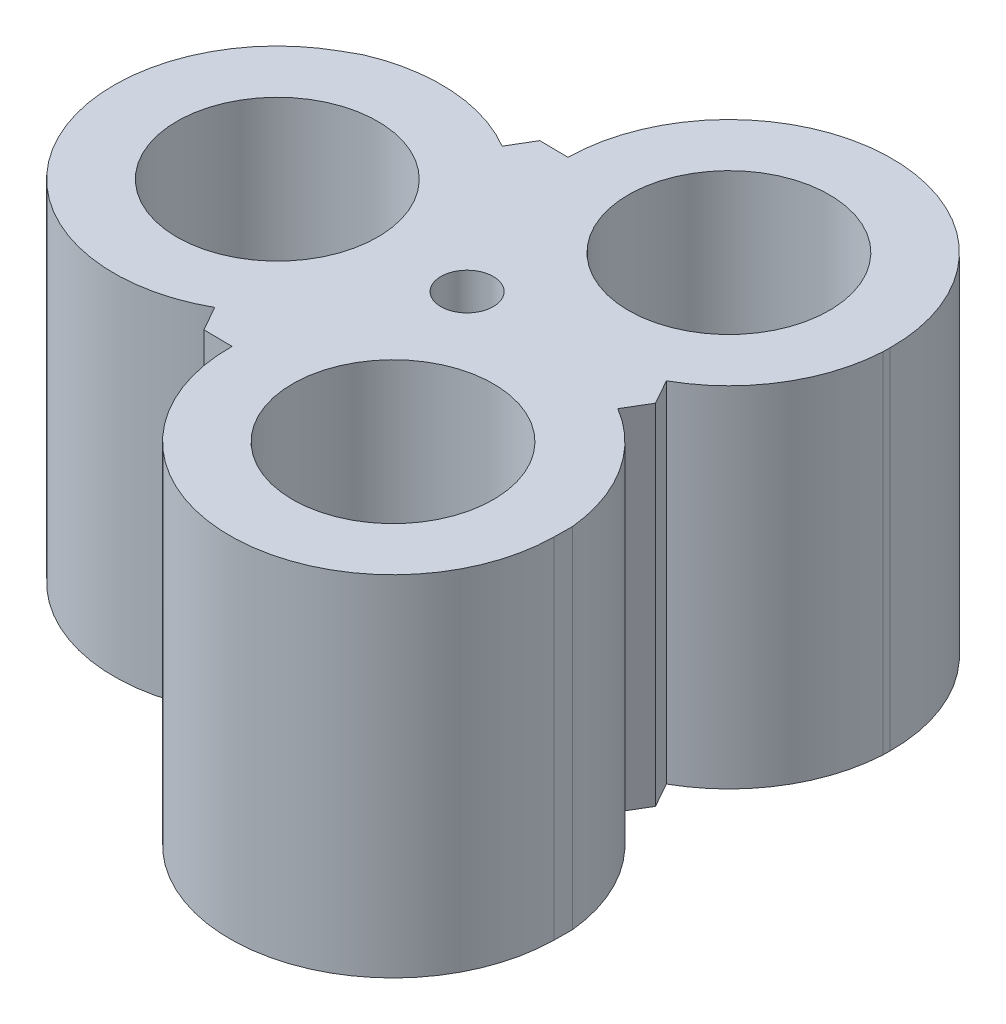
SolidWorks part; units mm, degrees
ref_plane "Front Plane" through (0, 0, 0) normal (0, 0, 1) x (1, 0, 0)
ref_plane "Top Plane" through (0, 0, 0) normal (0, 1, 0) x (1, 0, 0)
ref_plane "Right Plane" through (0, 0, 0) normal (1, 0, 0) x (0, 0, -1)
sketch "Sketch5" plane through (0, 0, 0) normal (0, 1, 0) x (1, 0, 0)
  circle A0 centre (0, 0) radius 30
  point P0 (0, 0)
  dimension "D1" = 60
extrude "Boss-Extrude1" add sketch "Sketch5" along normal blind 20
sketch "Sketch6" plane through (0, 20, 0) normal (0, 1, 0) x (1, 0, 0)
  circle A1 centre (5.5647, 9.4306) radius 5.75
  circle A2 centre (5.3253, -9.5678) radius 5.75
  circle A3 centre (-11.0082, 0.1387) radius 5.75
  dimension "D1" = 11.5
  dimension "D2" = 11.5
  dimension "D3" = 11.5
  dimension "D4" = 19
  dimension "D5" = 19
  dimension "D7" = 19
extrude "Cut-Extrude1" cut sketch "Sketch6" against normal blind 50
sketch "Sketch9" plane through (0, 20, 0) normal (0, 1, 0) x (1, 0, 0)
  line L0 (5.5647, 9.4306) -> (5.3253, -9.5678) construction
  line L1 (14.8992, 9.3131) -> (14.6599, -9.6854)
  line L3 (5.3253, -9.5678) -> (-11.0082, 0.1387) construction
  line L4 (0.5264, -17.6431) -> (-15.8071, -7.9366)
  line L6 (-11.0082, 0.1387) -> (5.5647, 9.4306) construction
  line L7 (-15.5778, 8.2888) -> (0.9951, 17.5808)
  arc A0 (14.8992, 9.3131) -> (-3.7699, 9.5482) centre (5.5647, 9.4306) ccw
  arc A1 (-4.0093, -9.4502) -> (14.6599, -9.6854) centre (5.3253, -9.5678) ccw
  arc A2 (0.5264, -17.6431) -> (10.1242, -1.4926) centre (5.3253, -9.5678) ccw
  arc A3 (-6.2093, 8.2139) -> (-15.8071, -7.9366) centre (-11.0082, 0.1387) ccw
  arc A4 (-15.5778, 8.2888) -> (-6.4386, -8.0115) centre (-11.0082, 0.1387) ccw
  arc A5 (10.1342, 1.2805) -> (0.9951, 17.5808) centre (5.5647, 9.4306) ccw
  point P4 (5.445, -0.0686)
  point P9 (-2.8414, -4.7146)
  point P17 (-2.7218, 4.7847)
extrude "Cut-Extrude-Thin1" cut sketch "Sketch9" against normal blind 50 thin thin type one direction wall 10
sketch "Sketch10" plane through (0, 20, 0) normal (0, 1, 0) x (1, 0, 0)
  circle A0 centre (5.3253, -9.5678) radius 5.75
  circle A1 centre (-11.0082, 0.1387) radius 5.75
  dimension "D1" = 11.5
  dimension "D2" = 11.5
sketch "Sketch11" plane through (0, 20, 0) normal (0, 1, 0) x (1, 0, 0)
  circle A0 centre (0, 0) radius 1.5
  dimension "D1" = 3
extrude "Cut-Extrude2" cut sketch "Sketch11" against normal through all
